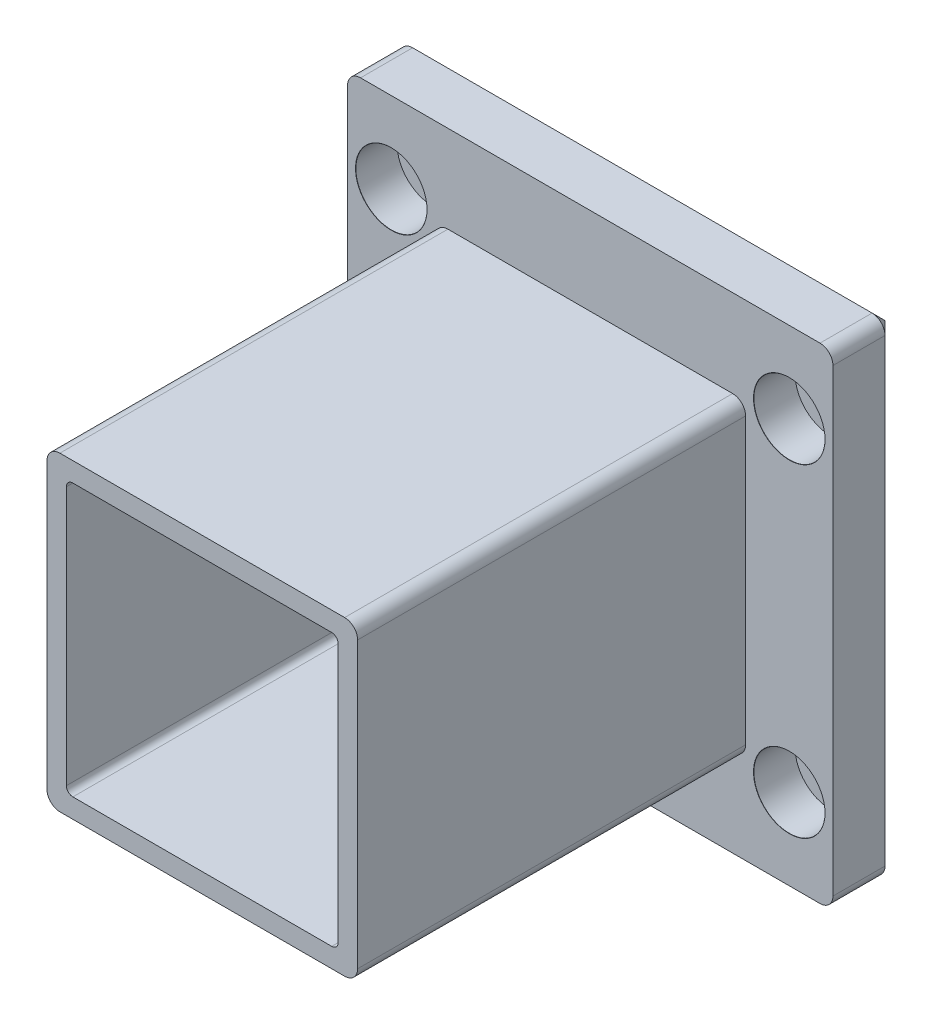
SolidWorks part; units mm, degrees
ref_plane "Front Plane" through (0, 0, 0) normal (1, 0, 0) x (0, 1, 0)
ref_plane "Top Plane" through (0, 0, 0) normal (0, 0, 1) x (0, 1, 0)
ref_plane "Right Plane" through (0, 0, 0) normal (0, 1, 0) x (-1, 0, 0)
sketch "Sketch1" plane through (0, 0, 0) normal (0, 0, 1) x (0, 1, 0)
  line L0 (-25.048, 30.1461) -> (-26.1566, 30.1461)
  line L1 (-25.048, 30.1461) -> (22.952, 30.1461)
  line L2 (-25.048, 30.1461) -> (-25.048, -17.8539)
  line L3 (-25.048, -17.8539) -> (22.952, -17.8539)
  line L4 (22.952, 30.1461) -> (22.952, -17.8539)
  line L6 (22.952, 30.1461) -> (15.3397, 30.1461)
  line L8 (-22.048, 27.1461) -> (-22.048, -14.8539)
  line L9 (-22.048, -14.8539) -> (19.952, -14.8539)
  line L10 (19.952, 27.1461) -> (19.952, -14.8539)
  line L11 (-22.048, 27.1461) -> (19.952, 27.1461)
  dimension "D1" = 42
  dimension "D2" = 42
  dimension "D3" = 3
extrude "Boss-Extrude1" add sketch "Sketch1" along normal blind 65 contours L4 L1 L0 L2 L3 L8 L11 L10 L9
sketch "Sketch3" plane through (0, 0, 0) normal (0, 0, -1) x (1, 0, 0)
  line L0 (-6.1461, 25.048) -> (-6.1461, -22.952)
  line L1 (-30.1461, 25.048) -> (17.8539, 25.048) construction
  line L2 (-30.1461, -22.952) -> (17.8539, -22.952) construction
  line L3 (17.8539, 25.048) -> (31.3539, 38.548)
  line L4 (-43.6461, 38.548) -> (31.3539, 38.548)
  line L5 (-43.6461, 38.548) -> (-43.6461, -36.452)
  line L6 (-43.6461, -36.452) -> (31.3539, -36.452)
  line L7 (31.3539, 38.548) -> (31.3539, -36.452)
  line L8 (-43.6461, 38.548) -> (31.3539, -36.452) construction
  line L9 (-43.6461, -36.452) -> (31.3539, 38.548) construction
  line L10 (24.6039, -23.952) -> (24.6039, 26.048)
  line L11 (24.6039, -29.702) -> (24.6039, 31.798)
  line L12 (-31.1461, 31.798) -> (18.8539, 31.798)
  line L13 (-36.8961, -23.952) -> (-36.8961, 26.048)
  line L14 (18.8539, -29.702) -> (-31.1461, -29.702)
  point P6 (-6.1461, 1.048)
  point P22 (24.6039, 1.048)
  dimension "D1" = 50
  dimension "D2" = 75
extrude "Boss-Extrude2" add sketch "Sketch3" along normal blind 5
sketch "Sketch8" plane through (0, 0, 0) normal (0, 0, 1) x (1, 0, 0)
  line L1 (-43.6461, 36.452) -> (31.3539, 36.452)
  line L2 (-43.6461, 36.452) -> (-43.6461, -38.548)
  line L3 (-43.6461, -38.548) -> (31.3539, -38.548)
  line L4 (31.3539, 36.452) -> (31.3539, -38.548)
  line L5 (-27.1461, 19.952) -> (14.8539, 19.952)
  line L6 (-27.1461, 19.952) -> (-27.1461, -22.048)
  line L7 (-27.1461, -22.048) -> (14.8539, -22.048)
  line L8 (14.8539, 19.952) -> (14.8539, -22.048)
extrude "Boss-Extrude3" add sketch "Sketch8" along normal blind 5.0471
fillet "Fillet1" radius 2 8 edges at (17.8539, -25.048, 35.0235) (17.8539, 22.952, 35.0235) (31.3539, 36.452, 0.0235) (-43.6461, 36.452, 0.0235) (-43.6461, -38.548, 0.0235) (31.3539, -38.548, 0.0235) (-30.1461, 22.952, 35.0235) (-30.1461, -25.048, 35.0235)
sketch "Sketch13" plane through (0, 0, 5.0471) normal (0, 0, 1) x (1, 0, 0)
  line L0 (-36.8961, 23.952) -> (-36.8961, -26.048)
  line L1 (-31.1461, -31.798) -> (18.8539, -31.798)
  line L2 (-43.6461, 36.452) -> (31.3539, -38.548)
  line L3 (24.6039, 23.952) -> (24.6039, -26.048)
  line L4 (-31.1461, 29.702) -> (18.8539, 29.702)
  point P0 (-36.8961, 23.952)
  point P1 (-36.8961, -26.048)
  point P12 (24.6039, 23.952)
  point P13 (24.6039, -26.048)
hole_wizard "CBORE for M6 Hex Socket Head Cap Screw2" positions "Sketch13" profile "Sketch15" counterbore size "M6" standard "ISO" end condition through all
sketch "Sketch15" plane through (-36.8961, 23.952, 5.0471) normal (1, 0, 0) x (0, -1, 0)
  line L0 (0, 0) -> (0, 10.0471)
  line L1 (0, 10.0471) -> (3.3, 10.0471)
  line L3 (3.3, 10.0471) -> (3.3, 6.4)
  line L4 (5.5, 6.4) -> (3.3, 6.4)
  line L5 (5.5, 6.4) -> (5.5, 0.025)
  line L6 (5.5, 0.025) -> (5.525, 0)
  line L7 (5.525, 0) -> (0, 0)
  line L8 (-5.5, 0.025) -> (-5.525, 0) construction
  line L11 (0, -6.35) -> (0, 107.95) construction
  dimension "Thru Hole Dia." = 6.6
  dimension "Thru Hole Depth" = 10.0471
  dimension "C'Bore Dia." = 11
  dimension "C'Bore Depth" = 6.4
  dimension "Near C'Sink Dia." = 11.05
  dimension "Near C'Sink Angle" = 90
fillet "Fillet2" radius 1 4 edges at (14.8539, -22.048, 32.5) (14.8539, 19.952, 32.5) (-27.1461, 19.952, 32.5) (-27.1461, -22.048, 32.5)
chamfer "Chamfer1" distance 2 angle 45 8 edges at (-43.6461, -1.048, -5) (-6.1461, -38.548, -5) (-6.1461, 36.452, -5) (-43.0603, -37.9622, -5) (-43.0603, 35.8662, -5) (30.7681, -37.9622, -5) (30.7681, 35.8662, -5) (31.3539, -1.048, -5)
